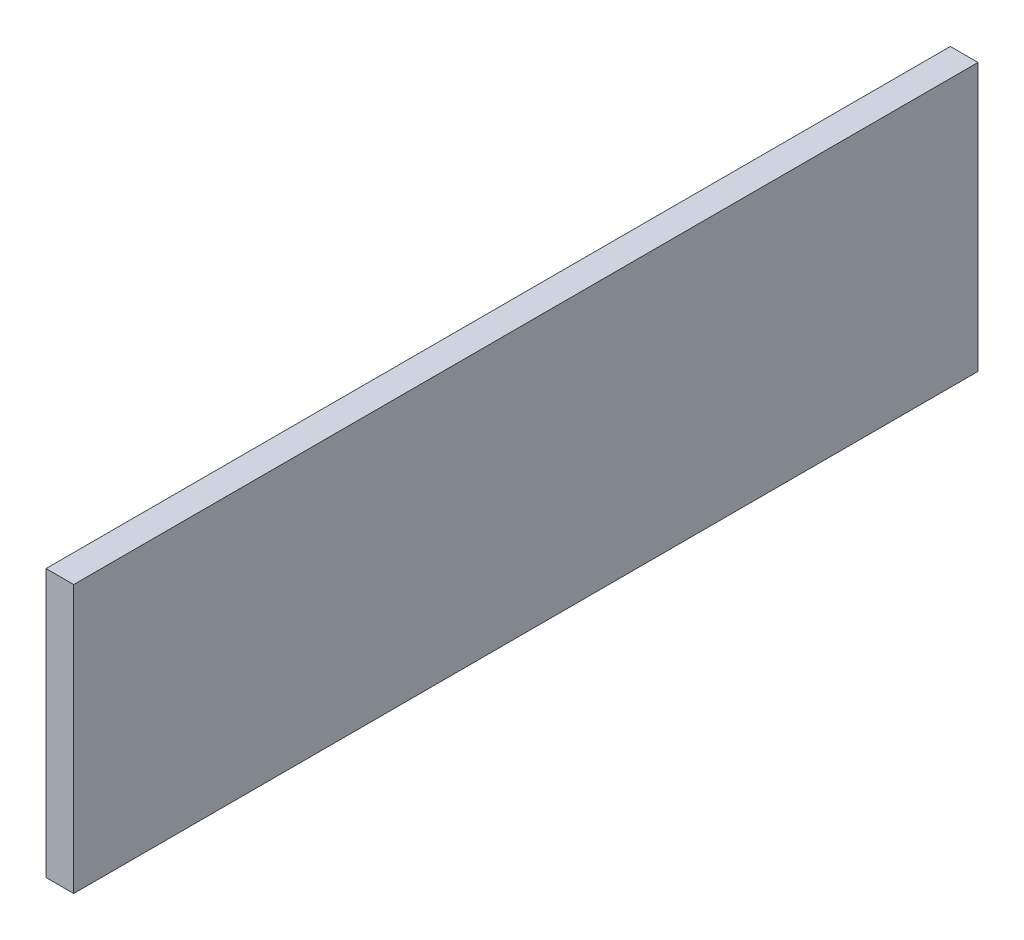
SolidWorks part; units mm, degrees
ref_plane "Front Plane" through (0, 0, 0) normal (0, 0, 1) x (1, 0, 0)
ref_plane "Top Plane" through (0, 0, 0) normal (0, 1, 0) x (1, 0, 0)
ref_plane "Right Plane" through (0, 0, 0) normal (1, 0, 0) x (0, 0, -1)
sketch "Sketch1" plane through (0, 0, 0) normal (1, 0, 0) x (0, 0, -1)
  line L1 (0, 0) -> (622.3, 0)
  line L2 (0, 0) -> (0, 184.15)
  line L3 (0, 184.15) -> (622.3, 184.15)
  line L4 (622.3, 0) -> (622.3, 184.15)
  dimension "D1" = 622.3
  dimension "D2" = 184.15
extrude "Boss-Extrude1" add sketch "Sketch1" along normal blind 19.05
